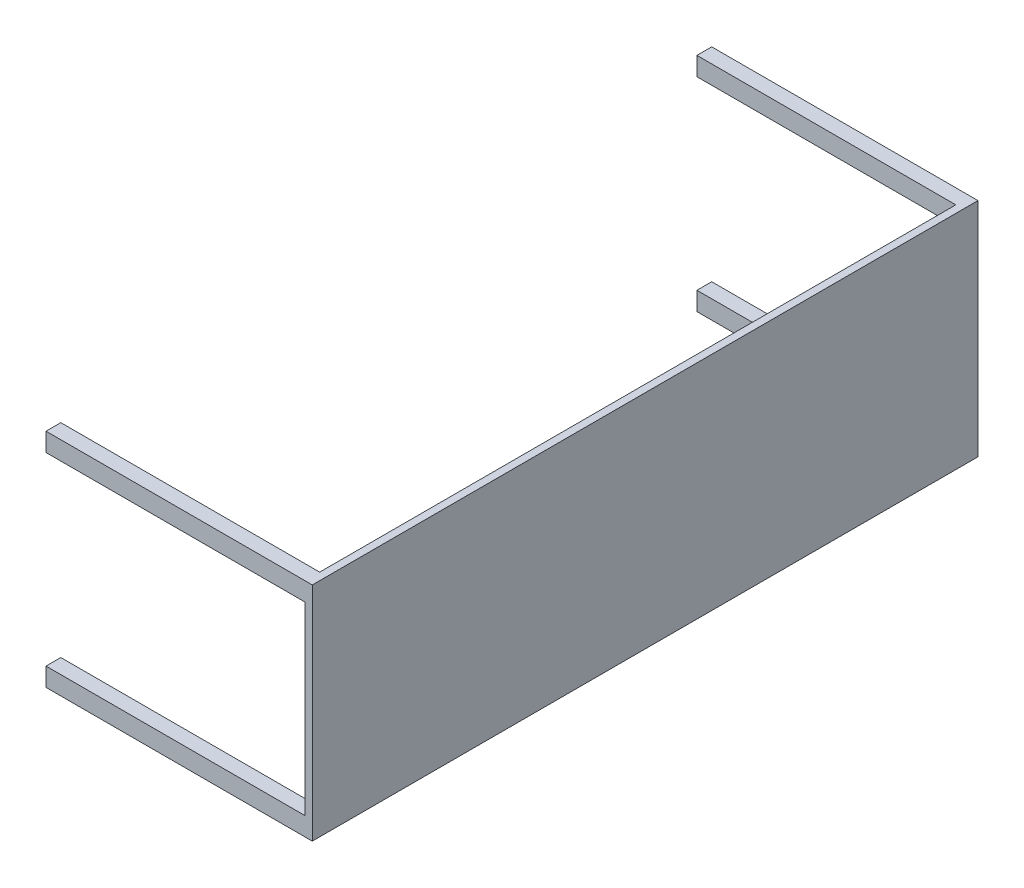
SolidWorks part; units mm, degrees
ref_plane "정면" through (0, 0, 0) normal (1, 0, 0) x (0, 1, 0)
ref_plane "윗면" through (0, 0, 0) normal (0, 0, 1) x (0, 1, 0)
ref_plane "우측면" through (0, 0, 0) normal (0, 1, 0) x (-1, 0, 0)
sketch "스케치1" plane through (0, 0, 0) normal (1, 0, 0) x (0, 1, 0)
  line L1 (-189.2548, 83.7088) -> (410.7452, 83.7088)
  line L2 (-189.2548, 83.7088) -> (-189.2548, -1716.2912)
  line L3 (-189.2548, -1716.2912) -> (410.7452, -1716.2912)
  line L4 (410.7452, 83.7088) -> (410.7452, -1716.2912)
  dimension "D1" = 600
  dimension "D2" = 1800
extrude "보스-돌출1" add sketch "스케치1" along normal blind 20
sketch "스케치2" plane through (0, 0, 0) normal (-1, 0, 0) x (0, -1, 0)
  line L0 (-410.7452, -1676.2912) -> (-360.7452, -1676.2912)
  line L1 (-410.7452, 83.7088) -> (-360.7452, 83.7088)
  line L2 (-410.7452, 83.7088) -> (-410.7452, 43.7088)
  line L3 (-410.7452, 43.7088) -> (-360.7452, 43.7088)
  line L4 (-360.7452, 83.7088) -> (-360.7452, 43.7088)
  line L5 (-410.7452, -1676.2912) -> (-410.7452, -1716.2912)
  line L6 (-410.7452, -1716.2912) -> (-360.7452, -1716.2912)
  line L7 (-360.7452, -1676.2912) -> (-360.7452, -1716.2912)
  line L8 (139.2548, 83.7088) -> (189.2548, 83.7088)
  line L9 (139.2548, 83.7088) -> (139.2548, 43.7088)
  line L10 (139.2548, 43.7088) -> (189.2548, 43.7088)
  line L11 (189.2548, 83.7088) -> (189.2548, 43.7088)
  line L12 (139.2548, -1676.2912) -> (189.2548, -1676.2912)
  line L13 (139.2548, -1676.2912) -> (139.2548, -1716.2912)
  line L14 (139.2548, -1716.2912) -> (189.2548, -1716.2912)
  line L15 (189.2548, -1676.2912) -> (189.2548, -1716.2912)
  point P9 (0, 0)
  point P15 (0, 0)
  point P21 (0, 0)
  dimension "D1" = 50
  dimension "D2" = 40
extrude "보스-돌출2" add sketch "스케치2" along normal blind 700
